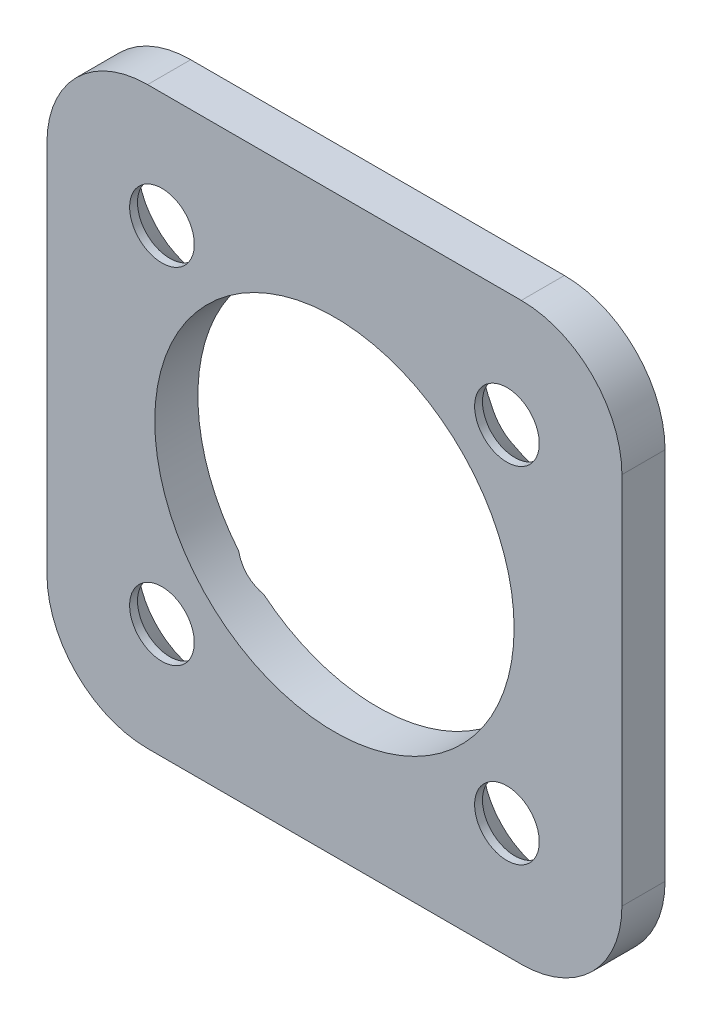
SolidWorks part; units mm, degrees
ref_plane "Front Plane" through (0, 0, 0) normal (0, 0, 1) x (1, 0, 0)
ref_plane "Top Plane" through (0, 0, 0) normal (0, 1, 0) x (1, 0, 0)
ref_plane "Right Plane" through (0, 0, 0) normal (1, 0, 0) x (0, 0, -1)
sketch "Sketch1" plane through (0, 0, 0) normal (0, 0, 1) x (1, 0, 0)
  line L1 (12, -12) -> (-12, -12) construction
  line L2 (-20, -20) -> (20, -20)
  line L3 (-20, -20) -> (-20, 20)
  line L4 (-20, 20) -> (20, 20)
  line L5 (20, -20) -> (20, 20)
  line L6 (-20, -20) -> (20, 20) construction
  line L7 (-20, 20) -> (20, -20) construction
  line L8 (12, -12) -> (12, 12) construction
  line L9 (12, 12) -> (-12, 12) construction
  line L10 (-12, -12) -> (-12, 12) construction
  line L11 (12, -12) -> (-12, 12) construction
  line L12 (12, 12) -> (-12, -12) construction
  circle A0 centre (0, 0) radius 12.5
  dimension "D1" = 24
  dimension "D2" = 24
extrude "Boss-Extrude1" add sketch "Sketch1" along normal blind 3
fillet "Fillet1" radius 7 4 edges at (-20, 20, 1.5) (-20, -20, 1.5) (20, -20, 1.5) (20, 20, 1.5)
hole_wizard "CSK for M4 Countersunk Flat Head Screw1" positions "Sketch2" profile "Sketch3" countersink size "M4" standard "ISO" end condition through all
sketch "Sketch2" plane through (0, 0, 0) normal (0, 0, -1) x (-1, 0, 0)
  point P0 (-12, 12)
  point P3 (12, 12)
  point P6 (12, -12)
  point P9 (-12, -12)
sketch "Sketch3" plane through (12, 12, 0) normal (1, 0, 0) x (0, 1, 0)
  line L0 (0, 0) -> (0, 3)
  line L1 (0, 3) -> (2.25, 3)
  line L2 (2.25, 3) -> (2.25, 2.45)
  line L3 (2.25, 2.45) -> (4.7, 0)
  line L5 (4.7, 0) -> (0, 0)
  line L6 (-2.25, 2.45) -> (-4.7, 0) construction
  line L11 (0, -6.35) -> (0, 107.95) construction
  dimension "Thru Hole Dia." = 4.5
  dimension "Thru Hole Depth" = 3
  dimension "Near C'Sink Dia." = 9.4
  dimension "Near C'Sink Angle" = 90
